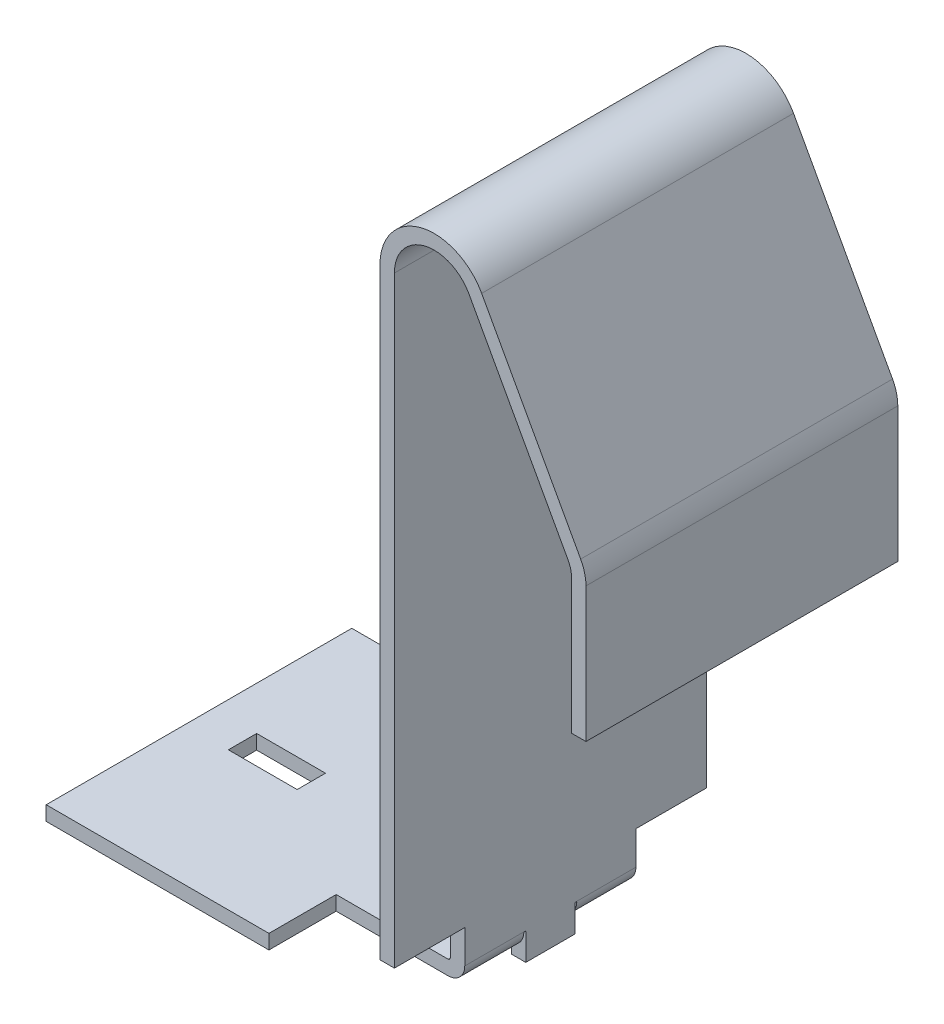
SolidWorks part; units mm, degrees
material "Saf Altın"
ref_plane "Ön Düzlem" through (0, 0, 0) normal (0, 0, 1) x (1, 0, 0)
ref_plane "Üst Düzlem" through (0, 0, 0) normal (0, 1, 0) x (1, 0, 0)
ref_plane "Sağ Düzlem" through (0, 0, 0) normal (1, 0, 0) x (0, 0, -1)
sketch "Çizim1" plane through (0, 0, 0) normal (0, 0, 1) x (1, 0, 0)
  line L0 (3.0903, 9.9103) -> (3.8707, 10.3381) construction
  line L1 (-0.3, 0.35) -> (-0.3, 13.55)
  line L2 (-36.2839, 13.5501) -> (-36.2839, 0.3548) construction
  line L3 (0.826, 13.55) -> (1.8134, 14.0912) construction
  line L4 (0.826, 13.55) -> (-0.3, 13.55) construction
  line L5 (1.8134, 14.0912) -> (3.8707, 10.3381)
  line L6 (3.9803, 9.9103) -> (3.9803, 7.1103)
  line L7 (3.0903, 9.9103) -> (3.9803, 9.9103) construction
  line L8 (-0.35, 0.3) -> (-7.3, 0.3)
  line L9 (-0.35, 0) -> (-7.3, 0)
  line L10 (0, 0.35) -> (0, 13.55)
  line L11 (1.5503, 13.947) -> (3.6076, 10.1939)
  line L12 (3.6803, 9.9103) -> (3.6803, 7.1103)
  line L13 (-7.3, 0.3) -> (-7.3, 0)
  line L14 (3.6803, 7.1103) -> (3.9803, 7.1103)
  line L21 (-36.2839, 0.0035) -> (-36.2839, -0.2248) construction
  line L22 (-36.2839, -0.2248) -> (-35.9791, -0.2195) construction
  line L23 (-35.9791, -0.2195) -> (-35.9791, 0.3548) construction
  line L24 (-43.2308, 0) -> (-38.6025, 0) construction
  line L25 (-38.6025, 0) -> (-38.6025, 0.3048) construction
  line L26 (-38.6025, 0.3048) -> (-43.2308, 0.3048) construction
  line L27 (-43.2308, 0.3048) -> (-43.2308, 0) construction
  line L28 (-36.2839, 1.0419) -> (-36.2839, 0.3548) construction
  line L29 (-36.3339, 0.3048) -> (-38.6025, 0.3048) construction
  line L30 (-38.6025, 0.3048) -> (-38.6025, 0) construction
  line L31 (-38.6025, 0) -> (-36.3339, 0) construction
  line L32 (-35.9791, 0.3548) -> (-35.9791, 1.0419) construction
  line L33 (-35.9791, 1.0419) -> (-36.2839, 1.0419) construction
  line L34 (-35.9791, 1.0419) -> (-35.9791, 13.5501) construction
  line L35 (-34.4379, 13.9448) -> (-32.3807, 10.1913) construction
  line L36 (-32.3088, 9.9105) -> (-32.3088, 7.112) construction
  line L37 (-32.3088, 7.112) -> (-32.004, 7.112) construction
  line L38 (-32.004, 7.112) -> (-32.004, 9.9105) construction
  line L39 (-32.1134, 10.3378) -> (-34.1706, 14.0913) construction
  line L40 (-36.2839, 13.5501) -> (-36.2839, 1.0419) construction
  line L41 (-36.2839, 1.0419) -> (-35.9791, 1.0419) construction
  arc A0 (-0.3, 13.55) -> (1.8134, 14.0912) centre (0.826, 13.55) cw
  arc A1 (3.8707, 10.3381) -> (3.9803, 9.9103) centre (3.0903, 9.9103) cw
  arc A2 (-0.3, 0.35) -> (-0.35, 0.3) centre (-0.35, 0.35) cw
  arc A3 (0, 0.35) -> (-0.35, 0) centre (-0.35, 0.35) cw
  arc A4 (0, 13.55) -> (1.5503, 13.947) centre (0.826, 13.55) cw
  arc A5 (3.6076, 10.1939) -> (3.6803, 9.9103) centre (3.0903, 9.9103) cw
  arc A7 (-36.2839, 0.0035) -> (-35.9791, 0.3548) centre (-36.3339, 0.3548) ccw construction
  arc A8 (-36.3339, 0.3048) -> (-36.2839, 0.3548) centre (-36.3339, 0.3548) ccw construction
  arc A9 (-36.3339, 0) -> (-35.9791, 0.3548) centre (-36.3339, 0.3548) ccw construction
  arc A10 (-34.4379, 13.9448) -> (-35.9791, 13.5501) centre (-35.158, 13.5501) ccw construction
  arc A11 (-32.3088, 9.9105) -> (-32.3807, 10.1913) centre (-32.893, 9.9105) ccw construction
  arc A12 (-32.004, 9.9105) -> (-32.1134, 10.3378) centre (-32.893, 9.9105) ccw construction
  arc A13 (-34.1706, 14.0913) -> (-36.2839, 13.5501) centre (-35.158, 13.5501) ccw construction
  dimension "D5" = 1.1259
  dimension "D6" = 1.126
  dimension "D8" = 0.889
  dimension "D11" = 0.89
  dimension "D15" = 0.05
  dimension "D1" = 13.5501
  dimension "D2" = 13.2
  dimension "D3" = 13.1953
  dimension "D4" = 13.1953
  dimension "D7" = 151.27
  dimension "D9" = 4.2802
  dimension "D10" = 4.28
  dimension "D12" = 2.7985
  dimension "D13" = 2.8
  dimension "D14" = 6.9469
  dimension "D16" = 6.95
  dimension "D17" = 0.3
extrude "Yükseklik-Ekstrüzyon1" add sketch "Çizim1" along normal mid plane 6.48
sketch "Çizim2" plane through (0, 0, 0) normal (0, 1, 0) x (1, 0, 0)
  line L1 (-7.3, -3.24) -> (-7.3, 3.24) construction
  line L2 (0, -3.24) -> (0, 3.24) construction
  line L3 (0, -4) -> (0, -1.778)
  line L4 (0, 4) -> (-8, 4)
  line L5 (-8, 4) -> (-8, -4)
  line L6 (-8, -4) -> (0, -4)
  line L7 (0, 1.778) -> (0, 4)
  line L13 (-2.6717, 1.778) -> (-2.6717, 3.175)
  line L14 (0, 1.778) -> (-2.6717, 1.778)
  line L15 (-2.6717, 3.175) -> (-7.3, 3.175)
  line L16 (-7.3, 3.175) -> (-7.3, -3.175)
  line L17 (-7.3, -3.175) -> (-2.6717, -3.175)
  line L18 (-2.6717, -3.175) -> (-2.6717, -1.778)
  line L19 (-2.6717, -1.778) -> (0, -1.778)
  line L20 (-4.966, -0.2942) -> (-4.966, 0.2942)
  line L21 (-4.966, 0.2942) -> (-6.396, 0.2942)
  line L22 (-6.396, 0.2942) -> (-6.396, -0.2942)
  line L23 (-6.396, -0.2942) -> (-4.966, -0.2942)
  point P18 (-4.966, 0)
  dimension "D1" = 0.5883
  dimension "D2" = 1.43
  dimension "D3" = 4.6283
  dimension "D5" = 1.397
  dimension "D6" = 1.397
  dimension "D7" = 6.35
  dimension "D8" = 0.904
  dimension "D9" = 2.8808
  dimension "D4" = 4
  dimension "D10" = 8
  dimension "D11" = 8
extrude "Kes-Ekstrüzyon1" cut sketch "Çizim2" along normal blind 1.0419
sketch "Çizim4" plane through (0, 0, 0) normal (1, 0, 0) x (0, 0, -1)
  line L0 (-1.778, 0.35) -> (1.778, 0.35) construction
  line L1 (-0.55, -0.15) -> (0.55, -0.15)
  line L2 (-0.55, -0.15) -> (-0.55, 0.33)
  line L3 (-0.53, 0.35) -> (0.53, 0.35)
  line L4 (0.55, -0.15) -> (0.55, 0.33)
  arc A0 (0.53, 0.35) -> (0.55, 0.33) centre (0.53, 0.33) cw
  arc A1 (-0.55, 0.33) -> (-0.53, 0.35) centre (-0.53, 0.33) cw
  dimension "D4" = 0.02
  dimension "D1" = 1.1
  dimension "D2" = 0.55
  dimension "D3" = 0.5
extrude "Kes-Ekstrüzyon2" cut sketch "Çizim4" against normal blind 0.5
sketch "Çizim5" plane through (0, 0, 0) normal (1, 0, 0) x (0, 0, -1)
  line L0 (0.53, 0.35) -> (-0.53, 0.35) construction
  line L1 (-0.51, -0.22) -> (0.51, -0.22)
  line L2 (-0.51, -0.22) -> (-0.51, 0.33)
  line L3 (-0.53, 0.35) -> (0.53, 0.35)
  line L4 (0.51, -0.22) -> (0.51, 0.33)
  line L5 (-0.51, -0.22) -> (0.51, 0.35) construction
  line L6 (-0.51, 0.35) -> (0.51, -0.22) construction
  line L7 (-1.778, 0.35) -> (-0.53, 0.35) construction
  arc A0 (-0.53, 0.35) -> (-0.51, 0.33) centre (-0.53, 0.33) cw
  arc A1 (0.53, 0.35) -> (0.51, 0.33) centre (0.53, 0.33) ccw
  point P0 (0, 0.065)
  dimension "D1" = 1.02
  dimension "D2" = 0.57
  dimension "D3" = 0.02
extrude "Yükseklik-Ekstrüzyon2" add sketch "Çizim5" against normal blind 0.3
equation "\"D10@Çizim2\"=2*\"D4@Çizim2\""
equation "\"D2@Çizim4\"=\"D1@Çizim4\"/2"
